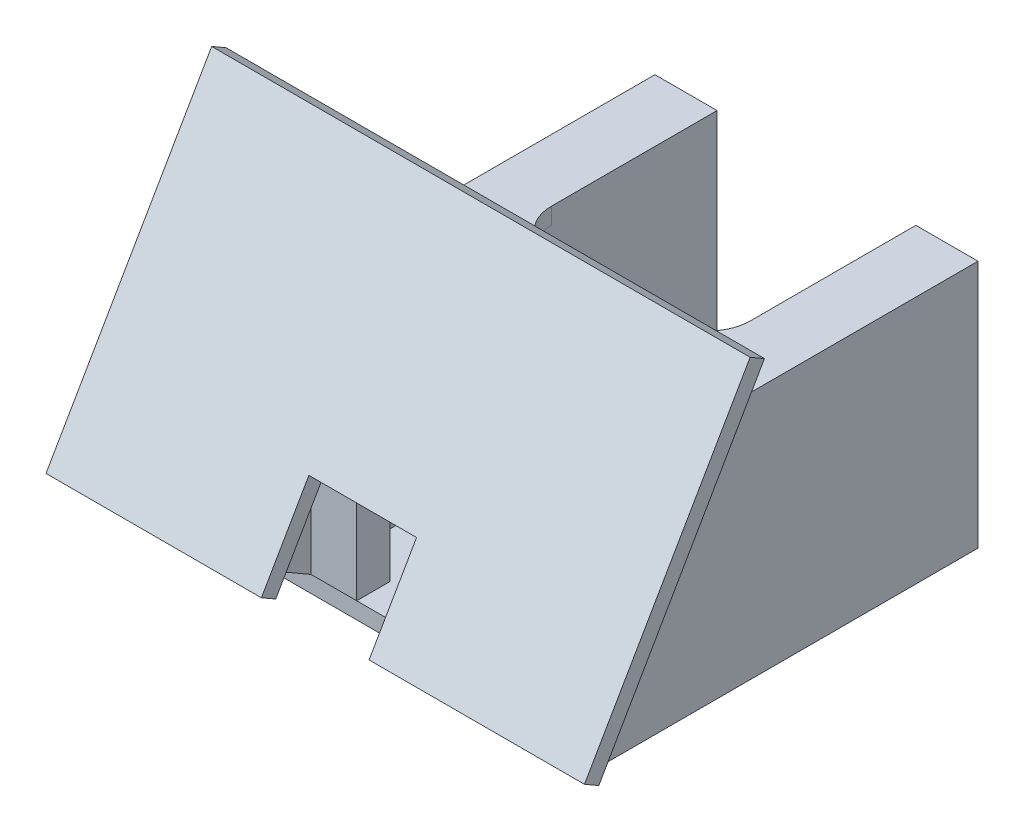
SolidWorks part; units mm, degrees
ref_plane "正面" through (0, 0, 0) normal (0, 0, 1) x (1, 0, 0)
ref_plane "平面" through (0, 0, 0) normal (0, 1, 0) x (1, 0, 0)
ref_plane "右側面" through (0, 0, 0) normal (1, 0, 0) x (0, 0, -1)
sketch "ｽｹｯﾁ1" plane through (0, 0, 0) normal (0, 0, 1) x (1, 0, 0)
  line L0 (-12, 0) -> (-12, 22)
  line L1 (-12, 22) -> (12, 22)
  line L2 (12, 22) -> (12, 0)
  line L3 (-12, 0) -> (-17.5, 0)
  line L4 (-17.5, 0) -> (-17.5, -4)
  line L5 (-17.5, -4) -> (17.5, -4)
  line L6 (17.5, -4) -> (17.5, 0)
  line L7 (17.5, 0) -> (12, 0)
  line L8 (-14, 24) -> (-14, 2)
  line L9 (-14, 2) -> (-19.5, 2)
  line L10 (-19.5, 2) -> (-19.5, -6)
  line L11 (-19.5, -6) -> (19.5, -6)
  line L12 (19.5, -6) -> (19.5, 2)
  line L13 (19.5, 2) -> (14, 2)
  line L14 (14, 2) -> (14, 24)
  line L15 (14, 24) -> (-14, 24)
  point P2 (0, 22)
  point P5 (0, -4)
  dimension "D1" = 24
  dimension "D2" = 22
  dimension "D3" = 35
  dimension "D4" = 4
  dimension "D5" = 2
  dimension "D6" = 2
  dimension "D7" = 2
  dimension "D8" = 2
  dimension "D9" = 2
  dimension "D10" = 2
  dimension "D11" = 2
extrude "ﾎﾞｽ - 押し出し1" add sketch "ｽｹｯﾁ1" along normal blind 45
sketch "ｽｹｯﾁ2" plane through (0, 0, 45) normal (0, 0, 1) x (1, 0, 0)
  line L0 (-14, 24) -> (-14, 0)
  line L1 (-12, 0) -> (-17.5, 0) construction
  line L2 (-14, 0) -> (-6.5, 0)
  line L3 (-6.5, 0) -> (-6.5, 16)
  line L4 (-6.5, 16) -> (6.5, 16)
  line L5 (6.5, 16) -> (6.5, 0)
  line L6 (6.5, 0) -> (14, 0)
  line L7 (17.5, 0) -> (12, 0) construction
  line L8 (14, 0) -> (14, 24)
  line L9 (14, 24) -> (-14, 24)
  line L10 (12, 22) -> (-12, 22) construction
  point P16 (0, 16)
  dimension "D1" = 6
  dimension "D2" = 13
extrude "ﾎﾞｽ - 押し出し2" add sketch "ｽｹｯﾁ2" along normal blind 4
sketch "ｽｹｯﾁ3" plane through (0, 0, 0) normal (0, 0, -1) x (-1, 0, 0)
  line L0 (-14, 24) -> (14, 24) construction
  line L1 (-12, 22) -> (12, 22)
  line L2 (-12, 22) -> (-12, 24)
  line L3 (-12, 24) -> (12, 24)
  line L4 (12, 22) -> (12, 24)
  line L5 (-12, 22) -> (12, 22) construction
  line L6 (-12, 22) -> (12, 22) construction
  line L7 (12, 22) -> (12, 0) construction
extrude "ｶｯﾄ - 押し出し1" cut sketch "ｽｹｯﾁ3" against normal blind 25
sketch "ｽｹｯﾁ4" plane through (14, 0, 0) normal (1, 0, 0) x (0, 0, -1)
  line L0 (-49, 24) -> (-50.0981, 22.0981)
  line L1 (-49, 0) -> (-49, 24) construction
  dimension "D1" = 30
ref_plane "平面1" through (0, 27.2176, 47.1423) normal (0, 0.5, 0.866) x (0, -0.866, 0.5)
sketch "ｽｹｯﾁ5" plane through (0, 27.2176, 47.1423) normal (0, 0.5, 0.866) x (0, -0.866, 0.5)
  line L1 (-15, 32.5) -> (25, 32.5)
  line L2 (-15, 32.5) -> (-15, -32.5)
  line L3 (-15, -32.5) -> (25, -32.5)
  line L4 (25, 32.5) -> (25, -32.5)
  point P4 (-15, 0)
  dimension "D1" = 65
  dimension "D2" = 15
  dimension "D3" = 25
extrude "ﾎﾞｽ - 押し出し3" add sketch "ｽｹｯﾁ5" along normal mid plane 2 separate body
sketch "ｽｹｯﾁ6" plane through (0, 0, 49) normal (0, 0, 1) x (1, 0, 0)
  line L1 (-6.5, 0) -> (6.5, 0)
  line L2 (-6.5, 0) -> (-6.5, 16)
  line L3 (-6.5, 16) -> (6.5, 16)
  line L4 (6.5, 0) -> (6.5, 16)
extrude "ｶｯﾄ - 押し出し2" cut sketch "ｽｹｯﾁ6" against normal through all both and the other way through all
sketch "ｽｹｯﾁ11" plane through (-14, 0, 0) normal (-1, 0, 0) x (0, 0, 1)
  line L0 (40.3453, 36.9904) -> (32.8453, 24)
  line L1 (38.7763, 39.708) -> (58.7763, 5.067) construction
  line L2 (49, 24) -> (0, 24) construction
  line L3 (32.8453, 24) -> (47.8453, 24)
  line L4 (47.8453, 24) -> (40.3453, 36.9904)
  dimension "D1" = 15
  dimension "D2" = 15
extrude "ﾎﾞｽ - 押し出し6" add sketch "ｽｹｯﾁ11" against normal blind 2
sketch "ｽｹｯﾁ12" plane through (14, 0, 0) normal (1, 0, 0) x (0, 0, -1)
  line L0 (-47.8453, 24) -> (-32.8453, 24)
  line L1 (-47.8453, 24) -> (0, 24) construction
  line L2 (-32.8453, 24) -> (-40.3453, 36.9904)
  line L3 (-47.8453, 24) -> (-40.3453, 36.9904) construction
  line L4 (-40.3453, 36.9904) -> (-47.8453, 24)
  dimension "D1" = 15
  dimension "D2" = 15
extrude "ﾎﾞｽ - 押し出し7" add sketch "ｽｹｯﾁ12" against normal blind 2
sketch "ｽｹｯﾁ13" plane through (-14, 0, 0) normal (-1, 0, 0) x (0, 0, 1)
  line L0 (49, 22) -> (49, 0)
  line L1 (49, 22) -> (49, 0) construction
  line L2 (49, 0) -> (58.5263, 5.5)
  line L3 (38.7763, 39.708) -> (58.7763, 5.067) construction
  line L4 (58.5263, 5.5) -> (49, 22)
extrude "ﾎﾞｽ - 押し出し8" add sketch "ｽｹｯﾁ13" against normal blind 2
sketch "ｽｹｯﾁ14" plane through (14, 0, 0) normal (1, 0, 0) x (0, 0, -1)
  line L0 (-49, 22) -> (-49, 0)
  line L1 (-49, 0) -> (-58.5263, 5.5)
  line L2 (-58.5263, 5.5) -> (-49, 22)
extrude "ﾎﾞｽ - 押し出し9" add sketch "ｽｹｯﾁ14" against normal blind 2
fillet "ﾌｨﾚｯﾄ1" radius 5 2 edges at (12, 23, 25) (-12, 23, 25)
sketch "ｽｹｯﾁ16" plane through (-14, 0, 0) normal (-1, 0, 0) x (0, 0, 1)
  line L0 (0, 24) -> (0, 2)
  line L1 (0, 2) -> (45, 2)
  line L2 (45, 2) -> (45, 0)
  line L3 (45, 0) -> (49, 0)
  line L4 (49, 0) -> (58.5263, 5.5)
  line L5 (58.5263, 5.5) -> (40.3453, 36.9904)
  line L6 (40.3453, 36.9904) -> (32.8453, 24)
  line L7 (32.8453, 24) -> (0, 24)
extrude "ﾎﾞｽ - 押し出し10" add sketch "ｽｹｯﾁ16" along normal blind 5.5
sketch "ｽｹｯﾁ17" plane through (14, 0, 0) normal (1, 0, 0) x (0, 0, -1)
  line L0 (0, 24) -> (0, 2)
  line L1 (0, 2) -> (-45, 2)
  line L2 (-45, 2) -> (0, 2) construction
  line L3 (-45, 2) -> (-45, 0)
  line L4 (-45, 0) -> (-49, 0)
  line L5 (-49, 0) -> (-58.5263, 5.5)
  line L6 (-58.5263, 5.5) -> (-40.3453, 36.9904)
  line L7 (-32.8453, 24) -> (-40.3453, 36.9904) construction
  line L8 (-58.7763, 5.067) -> (-38.7763, 39.708) construction
  line L9 (-40.3453, 36.9904) -> (-32.8453, 24)
  line L10 (-32.8453, 24) -> (0, 24)
extrude "ﾎﾞｽ - 押し出し11" add sketch "ｽｹｯﾁ17" along normal blind 5.5
sketch "ｽｹｯﾁ18" plane through (0, 26.7176, 46.2763) normal (0, -0.5, -0.866) x (-1, 0, 0)
  line L0 (-12, -5.4474) -> (-12, -24.5) construction
  line L1 (12, -5.4474) -> (-12, -5.4474)
  line L2 (12, -5.4474) -> (12, -10.4474)
  line L3 (12, -10.4474) -> (-12, -10.4474)
  line L4 (-12, -5.4474) -> (-12, -10.4474)
  dimension "D1" = 5
extrude "ﾎﾞｽ - 押し出し13" add sketch "ｽｹｯﾁ18" along normal blind 3
fillet "ﾌｨﾚｯﾄ2" radius 5 2 edges at (19.5, 21.2452, 49.4358) (-19.5, 21.2452, 49.4358)
